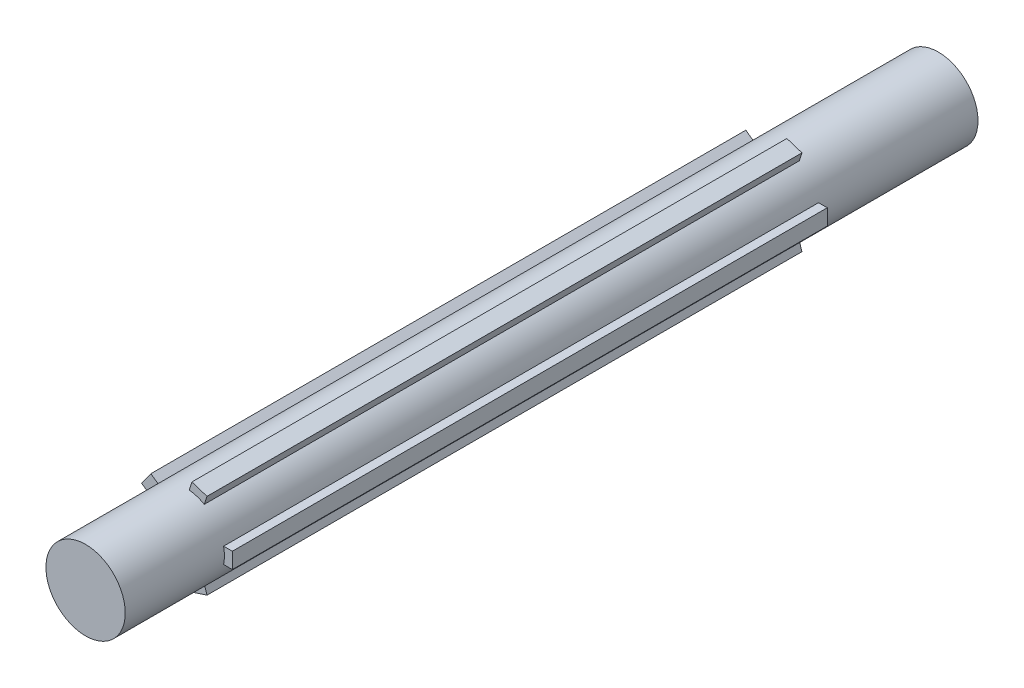
SolidWorks part; units mm, degrees
material "1023 Carbon Steel Sheet (SS)"
ref_plane "Front Plane" through (0, 0, 0) normal (0, 0, 1) x (1, 0, 0)
ref_plane "Top Plane" through (0, 0, 0) normal (0, 1, 0) x (1, 0, 0)
ref_plane "Right Plane" through (0, 0, 0) normal (1, 0, 0) x (0, 0, -1)
sketch "Sketch1" plane through (0, 0, 0) normal (0, 0, 1) x (1, 0, 0)
  line L1 (9.798, 2) -> (12, 2)
  line L3 (9.798, -2) -> (12, -2)
  line L4 (12, 2) -> (12, -2)
  line L5 (4.9298, -8.7004) -> (5.6103, -10.7946)
  line L6 (5.6103, -10.7946) -> (1.8061, -12.0307)
  line L7 (1.1256, -9.9364) -> (1.8061, -12.0307)
  line L9 (-6.7511, -7.3771) -> (-8.5326, -8.6715)
  line L10 (-8.5326, -8.6715) -> (-10.8838, -5.4354)
  line L11 (-9.1023, -4.1411) -> (-10.8838, -5.4354)
  line L13 (-9.1023, 4.1411) -> (-10.8838, 5.4354)
  line L14 (-10.8838, 5.4354) -> (-8.5326, 8.6715)
  line L15 (-6.7511, 7.3771) -> (-8.5326, 8.6715)
  line L17 (1.1256, 9.9364) -> (1.8061, 12.0307)
  line L18 (1.8061, 12.0307) -> (5.6103, 10.7946)
  line L19 (4.9298, 8.7004) -> (5.6103, 10.7946)
  arc A0 (-9.1023, 4.1411) -> (-9.1023, -4.1411) centre (0, 0) ccw
  arc A1 (9.798, 2) -> (4.9298, 8.7004) centre (0, 0) ccw
  arc A2 (4.9298, -8.7004) -> (9.798, -2) centre (0, 0) ccw
  arc A3 (-6.7511, -7.3771) -> (1.1256, -9.9364) centre (0, 0) ccw
  arc A4 (1.1256, 9.9364) -> (-6.7511, 7.3771) centre (0, 0) ccw
  point P2 (10, 0)
  point P27 (0, 0)
  dimension "D1" = 20
  dimension "D2" = 12
  dimension "D3" = 2
  dimension "D4" = 12
  dimension "D5" = 4
  dimension "D7" = 12
  dimension "D6" = 5
extrude "Boss-Extrude1" add sketch "Sketch1" against normal blind 150 contours A2 L3 L4 L1 A1 L19 L18 L17 A4 L15 L14 L13 A0 L11 L10 L9 A3 L7 L6 L5
sketch "Sketch2" plane through (0, 0, 0) normal (0, 0, 1) x (1, 0, 0)
  circle A0 centre (0, 0) radius 10
  dimension "D1" = 20
extrude "Boss-Extrude2" add sketch "Sketch2" along normal blind 25
sketch "Sketch3" plane through (0, 0, -150) normal (0, 0, -1) x (-1, 0, 0)
  circle A0 centre (0, 0) radius 10
  dimension "D1" = 20
extrude "Boss-Extrude3" add sketch "Sketch3" along normal blind 40
